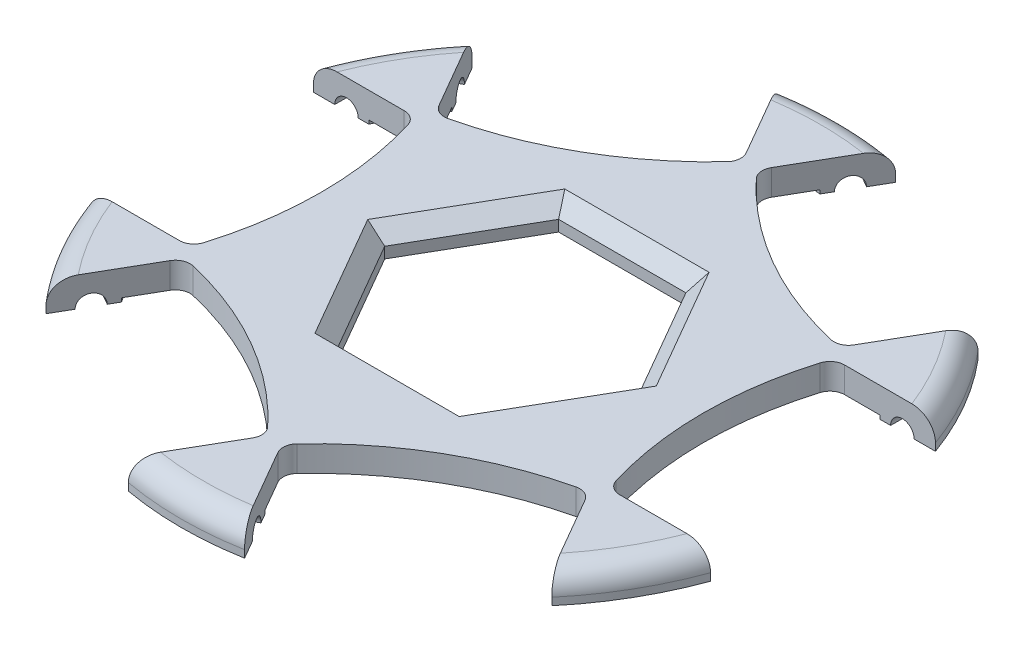
SolidWorks part; units mm, degrees
ref_plane "Ebene vorne" through (0, 0, 0) normal (0, 0, 1) x (1, 0, 0)
ref_plane "Ebene oben" through (0, 0, 0) normal (0, 1, 0) x (1, 0, 0)
ref_plane "Ebene rechts" through (0, 0, 0) normal (1, 0, 0) x (0, 0, -1)
sketch "Skizze1" plane through (0, 0, 0) normal (0, 1, 0) x (1, 0, 0)
  circle A0 centre (0, 0) radius 45
  dimension "D1" = 90
extrude "Aufsatz-Linear austragen1" add sketch "Skizze1" along normal blind 4
sketch "Skizze2" plane through (0, 4, 0) normal (0, 1, 0) x (1, 0, 0)
  line L0 (-28.5037, 15.3) -> (-71.0776, 15.3)
  line L1 (-28.5037, -15.3) -> (-71.0776, -15.3)
  line L2 (-71.0776, 15.3) -> (-71.0776, -15.3)
  circle A0 centre (-74, 0) radius 48
  circle M2 centre (0, 0) radius 45
  dimension "D1" = 74
  dimension "D2" = 96
  dimension "D3" = 30.6
  dimension "D4" = 15.3
extrude "Schnitt-Linear austragen2" cut sketch "Skizze2" against normal blind 10 contours L1 A0 L0 M2
pattern_circular "Kreismuster1" count 6 over 360 about axis through (0, 0, 0) along (0, 1, 0) of "Schnitt-Linear austragen2"
sketch "Skizze3" plane through (0, 0, 0) normal (0, -1, 0) x (1, 0, 0)
  line L1 (17.3205, 0) -> (8.6603, 15)
  line L2 (8.6603, 15) -> (-8.6603, 15)
  line L3 (-8.6603, 15) -> (-17.3205, 0)
  line L4 (-17.3205, 0) -> (-8.6603, -15)
  line L5 (-8.6603, -15) -> (8.6603, -15)
  line L6 (8.6603, -15) -> (17.3205, 0)
  circle A0 centre (0, 0) radius 15 construction
  dimension "D1" = 30
extrude "Schnitt-Linear austragen3" cut sketch "Skizze3" against normal blind 10
fillet "Verrundung1" radius 2 12 edges at (-28.5037, 2, 15.3) (-1.0017, 2, 32.335) (1.0017, 2, 32.335) (27.5021, 2, 17.035) (28.5037, 2, 15.3) (28.5037, 2, -15.3) (27.5021, 2, -17.035) (1.0017, 2, -32.335) (-1.0017, 2, -32.335) (-27.5021, 2, -17.035) (-28.5037, 2, -15.3) (-27.5021, 2, 17.035)
sketch "Skizze4" [suppressed] plane through (0, 4, 0) normal (0, 1, 0) x (1, 0, 0)
  circle A0 centre (0, 0) radius 20.15
sketch "Skizze5" plane through (13.2502, 0, 7.65) normal (-0.866, 0, -0.5) x (-0.5, 0, 0.866)
  line L0 (-29.9647, 0) -> (-42.3191, 0) construction
  line L1 (-42.3191, 0) -> (-42.3191, 4) construction
  circle A0 centre (-37.8191, 0) radius 1.6
  dimension "D1" = 4.5
extrude "Schnitt-Linear austragen5" cut sketch "Skizze5" against normal blind 3.8 contours A0
fillet "Verrundung4" radius 0.5 1 edges at (35.4507, 0, -23.2023)
pattern_circular "Kreismuster2" count 6 over 360 about axis through (0, 0, 0) along (0, 1, 0) of "Schnitt-Linear austragen5", "Verrundung4"
sketch "Skizze6" plane through (0, 0, -15.3) normal (0, 0, 1) x (1, 0, 0)
  line L0 (29.9647, 0) -> (42.3191, 0) construction
  line L1 (42.3191, 0) -> (42.3191, 4) construction
  circle A0 centre (37.8191, 0) radius 1.6
  dimension "D1" = 4.5
extrude "Schnitt-Linear austragen6" cut sketch "Skizze6" against normal blind 3.8
fillet "Verrundung3" radius 0.5 1 edges at (37.8191, 1.6, -19.1)
pattern_circular "Kreismuster3" count 6 over 360 about axis through (0, 0, 0) along (0, 1, 0) of "Schnitt-Linear austragen6", "Verrundung3"
sketch "Skizze7" plane through (0, 0, 0) normal (0, -1, 0) x (1, 0, 0)
  circle A0 centre (0, 0) radius 38
extrude "Schnitt-Linear austragen7" cut sketch "Skizze7" against normal blind 0.5
chamfer "Fase1" distance 2 angle 45 6 edges at (0, 4, -15) (-12.9904, 4, -7.5) (-12.9904, 4, 7.5) (0, 4, 15) (12.9904, 4, 7.5) (12.9904, 4, -7.5)
fillet "Verrundung2" radius 3 6 edges at (0, 4, -45) (38.9711, 4, -22.5) (38.9711, 4, 22.5) (0, 4, 45) (-38.9711, 4, 22.5) (-38.9711, 4, -22.5)
sketch "Zentrierung" plane through (0, 0.5, 0) normal (0, -1, 0) x (1, 0, 0)
  circle A0 centre (0, 0) radius 20
